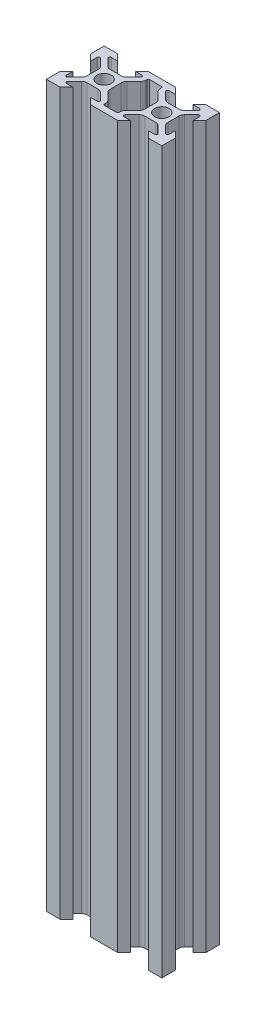
SolidWorks part; units mm, degrees
ref_plane "Front Plane" through (0, 0, 0) normal (0, 0, 1) x (1, 0, 0)
ref_plane "Top Plane" through (0, 0, 0) normal (0, 1, 0) x (1, 0, 0)
ref_plane "Right Plane" through (0, 0, 0) normal (1, 0, 0) x (0, 0, -1)
sketch "Sketch1" plane through (0, 0, 0) normal (0, -1, 0) x (0, 0, -1)
  line L0 (0, 0) -> (0, 10) construction
  line L1 (0, 10) -> (-10, 10) construction
  line L2 (-10, 10) -> (-10, 0) construction
  line L3 (-10, 0) -> (0, 0) construction
  line L4 (0, 0) -> (-10, 10) construction
  line L5 (-10, 10) -> (-10, 5.3)
  line L6 (-10, 5.3) -> (-7.8, 3.1)
  line L7 (-7.8, 3.1) -> (-7.8, 5.3201)
  line L8 (-6.9464, 5.6737) -> (-4.5858, 3.313)
  line L9 (-4, 1.8988) -> (-4, 0)
  line L10 (-10, 10) -> (-5.3, 10)
  line L11 (-5.3, 10) -> (-3.1, 7.8)
  line L12 (-3.1, 7.8) -> (-5.3201, 7.8)
  line L13 (-5.6737, 6.9464) -> (-3.313, 4.5858)
  line L14 (-1.8988, 4) -> (1.8988, 4)
  line L25 (5.6737, 6.9464) -> (3.313, 4.5858)
  line L26 (3.1, 7.8) -> (5.3201, 7.8)
  line L27 (5.3, 10) -> (3.1, 7.8)
  line L28 (10, 10) -> (5.3, 10)
  line L29 (4, 1.8988) -> (4, 0)
  line L40 (-7.8, -3.1) -> (-7.8, 3.1) construction
  line L41 (6.9464, 5.6737) -> (4.5858, 3.313)
  line L42 (7.8, 3.1) -> (7.8, 5.3201)
  line L43 (10, 5.3) -> (7.8, 3.1)
  line L44 (10, 10) -> (10, 5.3)
  line L48 (-5.6737, -6.9464) -> (-3.313, -4.5858)
  line L49 (-1.8988, -4) -> (1.8988, -4)
  line L50 (-10, -14.7) -> (-10, -5.3)
  line L51 (-10, -5.3) -> (-7.8, -3.1)
  line L52 (-7.8, -3.1) -> (-7.8, -5.3201)
  line L53 (-6.9464, -5.6737) -> (-4.5858, -3.313)
  line L54 (-4, -1.8988) -> (-4, 0)
  line L55 (-6.9464, -7.4737) -> (-7.3, -7.4737)
  line L56 (-10, 0) -> (-10, -10) construction
  line L57 (-10, -10) -> (0, -10) construction
  line L58 (4, -1.8988) -> (4, 0)
  line L59 (0, 0) -> (-10, -10) construction
  line L60 (-7.8, -7.9737) -> (-7.8, -12.0263)
  line L61 (7.8, -7.9737) -> (7.8, -12.0263)
  line L62 (6.9464, -7.4737) -> (7.3, -7.4737)
  line L63 (6.9464, -5.6737) -> (4.5858, -3.313)
  line L64 (7.8, -3.1) -> (7.8, -5.3201)
  line L65 (10, -5.3) -> (7.8, -3.1)
  line L66 (10, -14.7) -> (10, -5.3)
  line L67 (5.6737, -6.9464) -> (3.313, -4.5858)
  line L68 (0, 0) -> (0, -10) construction
  line L69 (5.6737, -13.0536) -> (3.313, -15.4142)
  line L70 (10, -14.7) -> (7.8, -16.9)
  line L71 (7.8, -16.9) -> (7.8, -14.6799)
  line L72 (6.9464, -14.3263) -> (4.5858, -16.687)
  line L73 (6.9464, -12.5263) -> (7.3, -12.5263)
  line L74 (4, -18.1012) -> (4, -20)
  line L75 (-6.9464, -12.5263) -> (-7.3, -12.5263)
  line L76 (-4, -18.1012) -> (-4, -20)
  line L77 (-6.9464, -14.3263) -> (-4.5858, -16.687)
  line L78 (-7.8, -16.9) -> (-7.8, -14.6799)
  line L79 (-10, -14.7) -> (-7.8, -16.9)
  line L80 (-1.8988, -16) -> (1.8988, -16)
  line L81 (-5.6737, -13.0536) -> (-3.313, -15.4142)
  line L82 (10, -30) -> (10, -25.3)
  line L83 (10, -25.3) -> (7.8, -23.1)
  line L84 (7.8, -23.1) -> (7.8, -25.3201)
  line L85 (6.9464, -25.6737) -> (4.5858, -23.313)
  line L86 (4, -21.8988) -> (4, -20)
  line L87 (10, -30) -> (5.3, -30)
  line L88 (5.3, -30) -> (3.1, -27.8)
  line L89 (3.1, -27.8) -> (5.3201, -27.8)
  line L90 (5.6737, -26.9464) -> (3.313, -24.5858)
  line L91 (-1.8988, -24) -> (1.8988, -24)
  line L92 (-5.6737, -26.9464) -> (-3.313, -24.5858)
  line L93 (-3.1, -27.8) -> (-5.3201, -27.8)
  line L94 (-5.3, -30) -> (-3.1, -27.8)
  line L95 (-10, -30) -> (-5.3, -30)
  line L96 (-4, -21.8988) -> (-4, -20)
  line L97 (-6.9464, -25.6737) -> (-4.5858, -23.313)
  line L98 (-7.8, -23.1) -> (-7.8, -25.3201)
  line L99 (-10, -25.3) -> (-7.8, -23.1)
  line L100 (-10, -30) -> (-10, -25.3)
  circle A0 centre (0, 0) radius 2.5
  arc A1 (-7.8, 5.3201) -> (-6.9464, 5.6737) centre (-7.3, 5.3201) cw
  arc A2 (-4.5858, 3.313) -> (-4, 1.8988) centre (-6, 1.8988) cw
  arc A3 (-5.3201, 7.8) -> (-5.6737, 6.9464) centre (-5.3201, 7.3) ccw
  arc A4 (-3.313, 4.5858) -> (-1.8988, 4) centre (-1.8988, 6) ccw
  arc A14 (-3.313, -4.5858) -> (-1.8988, -4) centre (-1.8988, -6) cw
  arc A15 (-7.8, -5.3201) -> (-6.9464, -5.6737) centre (-7.3, -5.3201) ccw
  arc A16 (-4.5858, -3.313) -> (-4, -1.8988) centre (-6, -1.8988) ccw
  arc A17 (3.313, 4.5858) -> (1.8988, 4) centre (1.8988, 6) cw
  arc A18 (5.3201, 7.8) -> (5.6737, 6.9464) centre (5.3201, 7.3) cw
  arc A19 (4.5858, 3.313) -> (4, 1.8988) centre (6, 1.8988) ccw
  arc A20 (7.8, 5.3201) -> (6.9464, 5.6737) centre (7.3, 5.3201) ccw
  arc A21 (-5.6737, -6.9464) -> (-6.9464, -7.4737) centre (-6.9464, -5.6737) cw
  arc A22 (-7.3, -7.4737) -> (-7.8, -7.9737) centre (-7.3, -7.9737) ccw
  arc A23 (7.3, -7.4737) -> (7.8, -7.9737) centre (7.3, -7.9737) cw
  arc A24 (5.6737, -6.9464) -> (6.9464, -7.4737) centre (6.9464, -5.6737) ccw
  arc A25 (4.5858, -3.313) -> (4, -1.8988) centre (6, -1.8988) cw
  arc A26 (7.8, -5.3201) -> (6.9464, -5.6737) centre (7.3, -5.3201) cw
  arc A27 (3.313, -4.5858) -> (1.8988, -4) centre (1.8988, -6) ccw
  arc A28 (3.313, -15.4142) -> (1.8988, -16) centre (1.8988, -14) cw
  arc A29 (7.8, -14.6799) -> (6.9464, -14.3263) centre (7.3, -14.6799) ccw
  arc A30 (4.5858, -16.687) -> (4, -18.1012) centre (6, -18.1012) ccw
  arc A31 (5.6737, -13.0536) -> (6.9464, -12.5263) centre (6.9464, -14.3263) cw
  arc A32 (7.3, -12.5263) -> (7.8, -12.0263) centre (7.3, -12.0263) ccw
  arc A33 (-7.3, -12.5263) -> (-7.8, -12.0263) centre (-7.3, -12.0263) cw
  arc A34 (-5.6737, -13.0536) -> (-6.9464, -12.5263) centre (-6.9464, -14.3263) ccw
  arc A35 (7.8, -25.3201) -> (6.9464, -25.6737) centre (7.3, -25.3201) cw
  arc A36 (4.5858, -23.313) -> (4, -21.8988) centre (6, -21.8988) cw
  arc A37 (5.3201, -27.8) -> (5.6737, -26.9464) centre (5.3201, -27.3) ccw
  arc A38 (3.313, -24.5858) -> (1.8988, -24) centre (1.8988, -26) ccw
  arc A39 (-4.5858, -16.687) -> (-4, -18.1012) centre (-6, -18.1012) cw
  arc A40 (-7.8, -14.6799) -> (-6.9464, -14.3263) centre (-7.3, -14.6799) cw
  arc A41 (-3.313, -15.4142) -> (-1.8988, -16) centre (-1.8988, -14) ccw
  arc A42 (-3.313, -24.5858) -> (-1.8988, -24) centre (-1.8988, -26) cw
  arc A43 (-5.3201, -27.8) -> (-5.6737, -26.9464) centre (-5.3201, -27.3) cw
  arc A44 (-4.5858, -23.313) -> (-4, -21.8988) centre (-6, -21.8988) ccw
  arc A45 (-7.8, -25.3201) -> (-6.9464, -25.6737) centre (-7.3, -25.3201) ccw
  circle A46 centre (0, -20) radius 2.5
  point P36 (0, 4)
  point P47 (-7.8, 0)
  point P49 (0, 0)
  point P70 (-7.8, -10)
  point P80 (0, -4)
  point P138 (10, -10)
  point P139 (7.8, -10)
  point P153 (0, -16)
  point P154 (0, -20)
  point P155 (-7.8, -20)
  point P156 (0, -24)
  dimension "D1" = 5
  dimension "D5" = 2
  dimension "D7" = 0.5
  dimension "D2" = 10
  dimension "D3" = 5.3
  dimension "D4" = 6
  dimension "D6" = 0.9
  dimension "D8" = 3.1
  dimension "D10" = 20
extrude "Boss-Extrude1" add sketch "Sketch1" against normal blind 250
